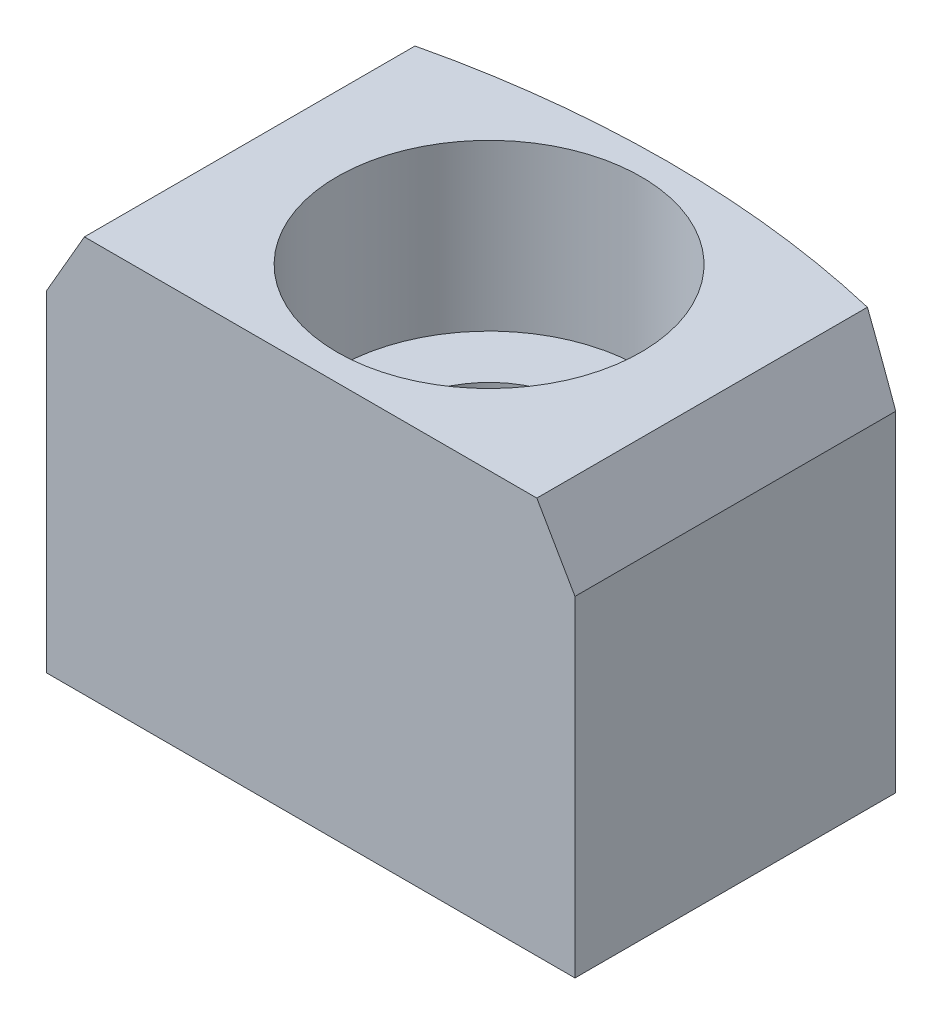
SolidWorks part; units mm, degrees
material "AISI 1020"
ref_plane "Front Plane" through (0, 0, 0) normal (0, 0, 1) x (1, 0, 0)
ref_plane "Top Plane" through (0, 0, 0) normal (0, 1, 0) x (1, 0, 0)
ref_plane "Right Plane" through (0, 0, 0) normal (1, 0, 0) x (0, 0, -1)
sketch "Sketch1" plane through (0, 0, 0) normal (0, 1, 0) x (1, 0, 0)
  line L0 (0, 0) -> (0, 31.023) construction
  line L1 (0, 0) -> (40.3178, 0) construction
  line L3 (-4, 3) -> (4, 3)
  line L4 (-4, 3) -> (-4, -2.7)
  line L5 (-4, -2.7) -> (4, -2.7)
  line L6 (4, 3) -> (4, -2.7)
  dimension "D1" = 4
  dimension "D2" = 4
  dimension "D3" = 3
  dimension "D4" = 2.7
extrude "Extruded Boss/Base" add sketch "Sketch1" along normal mid plane 6
hole_wizard "Legacy Hole" positions "Sketch3" profile "Sketch2" legacy end condition through all
sketch "Sketch3" plane through (0, 3, 0) normal (0, 1, 0) x (-1, 0, 0)
  point P0 (0, 0)
sketch "Sketch2" plane through (0, 3, 0) normal (1, 0, 0) x (0, 0, 1)
  line L0 (0, 0) -> (0, 6)
  line L1 (0, 6) -> (1.35, 6)
  line L3 (1.35, 6) -> (1.35, 2.5)
  line L4 (1.35, 2.5) -> (2.3, 2.5)
  line L5 (2.3, 2.5) -> (2.3, 0)
  line L7 (2.3, 0) -> (0, 0)
  line L11 (0, -6.35) -> (0, 107.95) construction
  dimension "Bohrerdurchmesser" = 2.7
  dimension "Bohrungstiefe" = 6
  dimension "Senkdurchmesser2" = 4.6
  dimension "Senktiefe2" = 2.5
chamfer "Fillet" distance 1 angle 30 2 edges at (4, 3, -0.15) (-4, 3, -0.15)
sketch "Sketch4" plane through (0, 3, 0) normal (0, 1, 0) x (1, 0, 0)
  line L0 (0, 0) -> (0, -9.4133) construction
  line L1 (0, 0) -> (5.4435, 0) construction
  circle A0 centre (0, -12.2) radius 14.9
  circle A1 centre (0, -12.2) radius 15.7175
  dimension "D1" = 29.8
  dimension "D2" = 12.2
extrude "Extruded Cut" cut sketch "Sketch4" against normal through all
